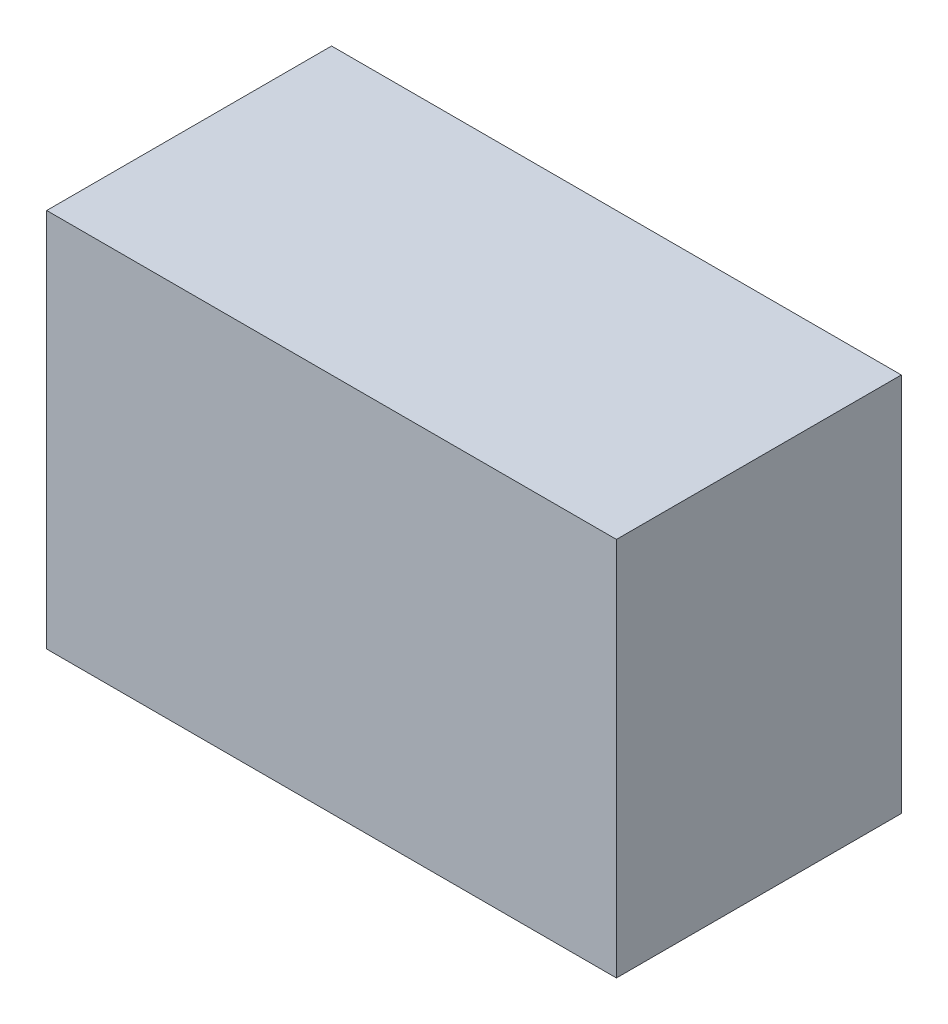
SolidWorks part; units mm, degrees
ref_plane "Plan1" through (0, 0, 0) normal (0, 0, 1) x (1, 0, 0)
ref_plane "Plan2" through (0, 0, 0) normal (0, 1, 0) x (1, 0, 0)
ref_plane "Plan3" through (0, 0, 0) normal (1, 0, 0) x (0, 0, -1)
sketch "Esquisse1" plane through (0, 0, 0) normal (0, 0, 1) x (1, 0, 0)
  line L1 (0, 0) -> (30, 0)
  line L2 (0, 0) -> (0, 20)
  line L3 (0, 20) -> (30, 20)
  line L4 (30, 0) -> (30, 20)
  dimension "D1" = 20
extrude "Base-Extrusion" add sketch "Esquisse1" along normal blind 15
